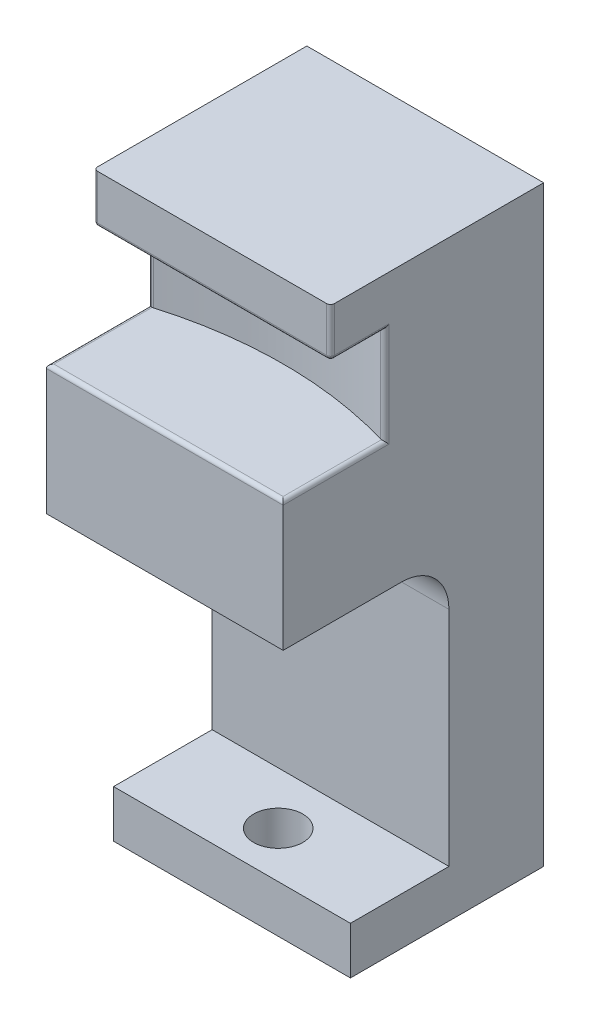
SolidWorks part; units mm, degrees
material "ABS"
ref_plane "Front Plane" through (0, 0, 0) normal (0, 0, 1) x (1, 0, 0)
ref_plane "Top Plane" through (0, 0, 0) normal (0, 1, 0) x (1, 0, 0)
ref_plane "Right Plane" through (0, 0, 0) normal (1, 0, 0) x (0, 0, -1)
sketch "Sketch1" plane through (0, 0, 0) normal (0, 0, 1) x (1, 0, 0)
  line L1 (0, 0) -> (15.875, 0)
  line L2 (0, 0) -> (0, 34.925)
  line L3 (0, 34.925) -> (15.875, 34.925)
  line L4 (15.875, 0) -> (15.875, 34.925)
  dimension "D1" = 15.875
  dimension "D2" = 34.925
extrude "Boss-Extrude1" add sketch "Sketch1" along normal blind 6.35
sketch "Sketch3" plane through (0, 0, 6.35) normal (0, 0, 1) x (1, 0, 0)
  line L0 (0, 34.925) -> (0, 0) construction
  line L1 (0, 16.51) -> (15.875, 16.51)
  line L2 (0, 16.51) -> (0, 34.925)
  line L3 (0, 34.925) -> (15.875, 34.925)
  line L4 (15.875, 16.51) -> (15.875, 34.925)
  line L5 (0, 0) -> (15.875, 0) construction
  dimension "D1" = 16.51
extrude "Boss-Extrude2" add sketch "Sketch3" along normal blind 7.9375
ref_plane "Plane1" through (0, 28.429, 0) normal (0, -1, 0) x (-1, 0, 0)
sketch "Sketch4" plane through (0, 28.429, 0) normal (0, -1, 0) x (-1, 0, 0)
  line L0 (0, 0) -> (-15.875, 0) construction
  line L1 (-15.875, -14.2875) -> (0, -14.2875) construction
  circle A0 centre (-7.9375, -36.4998) radius 26.9875
  point P5 (-7.9375, 0)
  point P9 (-7.9375, -14.2875)
  dimension "D2" = 53.975
  dimension "D1" = 36.4998
extrude "Cut-Extrude2" cut sketch "Sketch4" against normal mid plane 6.477
sketch "Sketch5" plane through (0, 0, 14.2875) normal (0, 0, 1) x (1, 0, 0)
  line L4 (15.875, 16.51) -> (15.875, 25.1905)
  line L5 (15.875, 25.1905) -> (0, 25.1905)
  line L6 (0, 25.1905) -> (0, 16.51)
  line L7 (0, 16.51) -> (15.875, 16.51)
  line L8 (15.875, 16.51) -> (15.875, 25.1905)
  line L9 (15.875, 25.1905) -> (0, 25.1905)
  line L10 (0, 25.1905) -> (0, 16.51)
  line L11 (0, 16.51) -> (15.875, 16.51)
  dimension "D1" = 0
extrude "Boss-Extrude3" add sketch "Sketch5" along normal blind 3.175
fillet "Fillet1" radius 0.254 10 edges at (15.875, 33.2962, 14.2875) (15.875, 31.6674, 12.4967) (7.9375, 31.6674, 14.2875) (0, 33.2962, 14.2875) (0, 31.6674, 12.4967) (0, 28.429, 10.706) (0, 25.1905, 14.0842) (15.875, 25.1905, 14.0842) (15.875, 28.429, 10.706) (7.9375, 25.1905, 17.4625)
fillet "Fillet2" radius 3.175 1 edges at (7.9375, 16.51, 6.35)
sketch "Sketch6" plane through (0, 0, 0) normal (0, -1, 0) x (1, 0, 0)
  line L4 (0, 0) -> (15.875, 0)
  line L5 (15.875, 0) -> (15.875, 6.35)
  line L6 (15.875, 6.35) -> (0, 6.35)
  line L7 (0, 6.35) -> (0, 0)
  line L8 (0, 0) -> (15.875, 0)
  line L9 (15.875, 0) -> (15.875, 6.35)
  line L10 (15.875, 6.35) -> (0, 6.35)
  line L11 (0, 6.35) -> (0, 0)
  dimension "D1" = 0
extrude "Boss-Extrude4" add sketch "Sketch6" along normal blind 4.7625
sketch "Sketch7" plane through (0, 0, 6.35) normal (0, 0, 1) x (1, 0, 0)
  line L0 (15.875, -4.7625) -> (15.875, 13.335) construction
  line L1 (0, -4.7625) -> (15.875, -4.7625)
  line L2 (0, -4.7625) -> (0, -1.5875)
  line L3 (0, -1.5875) -> (15.875, -1.5875)
  line L4 (15.875, -4.7625) -> (15.875, -1.5875)
  dimension "D1" = 3.175
extrude "Boss-Extrude5" add sketch "Sketch7" along normal blind 6.604
sketch "Sketch8" plane through (0, -4.7625, 0) normal (0, -1, 0) x (1, 0, 0)
  line L0 (0, 12.954) -> (15.875, 12.954) construction
  circle A0 centre (7.9375, 9.8552) radius 1.651
  point P5 (7.9375, 12.954)
  dimension "D2" = 3.302
  dimension "D1" = 3.0988
extrude "Cut-Extrude3" cut sketch "Sketch8" against normal up to next
